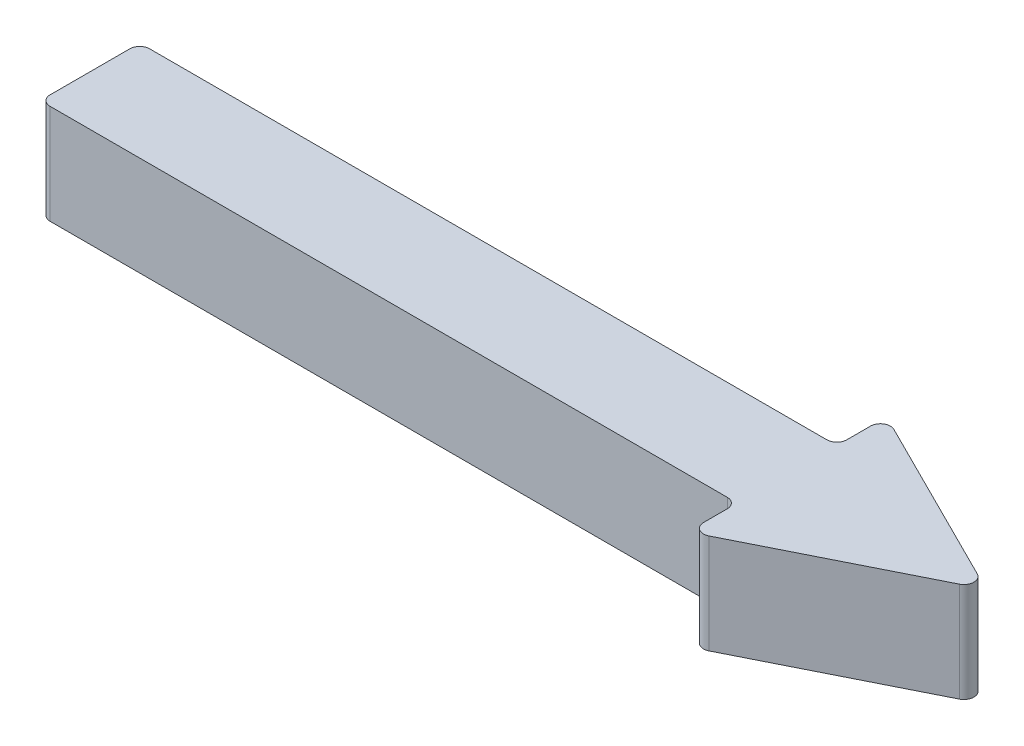
SolidWorks part; units mm, degrees
material "Acrylic (Medium-high impact)"
ref_plane "Front Plane" through (0, 0, 0) normal (0, 0, 1) x (1, 0, 0)
ref_plane "Top Plane" through (0, 0, 0) normal (0, 1, 0) x (1, 0, 0)
ref_plane "Right Plane" through (0, 0, 0) normal (1, 0, 0) x (0, 0, -1)
sketch "Sketch1" plane through (0, 0, 0) normal (0, 1, 0) x (1, 0, 0)
  line L0 (0, 3.175) -> (57.15, 3.175) construction
  line L1 (0, 0) -> (44.45, 0)
  line L2 (0, 0) -> (0, 6.35)
  line L3 (0, 6.35) -> (44.45, 6.35)
  line L4 (44.45, 0) -> (44.45, 6.35)
  line L5 (44.45, -3.175) -> (44.45, 9.525)
  line L6 (44.45, 9.525) -> (57.15, 3.175)
  line L7 (57.15, 3.175) -> (44.45, -3.175)
  point P10 (44.45, 3.175)
  dimension "D1" = 6.35
  dimension "D2" = 44.45
  dimension "D3" = 57.15
  dimension "D4" = 12.7
extrude "Boss-Extrude1" add sketch "Sketch1" along normal blind 6.35 contours L2 L0 L5 L3 | L0 L2 L1 L4 | L5 L0 L6 | L0 L4 L5 L7
sketch "Sketch2" plane through (0, 0, 0) normal (-1, 0, 0) x (0, 0, 1)
  line L0 (-3.175, 0) -> (-3.175, 6.35) construction
  line L1 (0, 6.35) -> (-6.35, 6.35) construction
  line L2 (-6.35, 3.175) -> (0, 3.175) construction
  line L3 (-6.35, 6.35) -> (-6.35, 0) construction
  line L4 (0, 6.35) -> (0, 0) construction
  circle A0 centre (-3.175, 3.175) radius 2.4003
  dimension "D1" = 4.8006
extrude "Cut-Extrude1" cut sketch "Sketch2" against normal blind 8.89
fillet "Fillet1" radius 0.635 7 edges at (44.45, 3.175, -6.35) (44.45, 3.175, 0) (44.45, 3.175, 3.175) (44.45, 3.175, -9.525) (57.15, 3.175, -3.175) (0, 3.175, 0) (0, 3.175, -6.35)
sketch "Sketch4" plane through (0, 0, 0) normal (0, -1, 0) x (1, 0, 0)
  line L0 (0, -3.175) -> (56.3651, -3.175) construction
  line L1 (0, -0.635) -> (0, -5.715) construction
  line L2 (28.1825, -6.35) -> (28.1825, 0)
  line L3 (0.635, 0) -> (43.815, 0) construction
  arc A0 (56.0141, -3.743) -> (56.0141, -2.607) centre (55.7301, -3.175) ccw construction
  circle A1 centre (20.5625, -3.175) radius 0.889
  circle A2 centre (35.8025, -3.175) radius 0.889
  point P12 (28.1825, -3.175)
  dimension "D1" = 1.778
  dimension "D2" = 7.62
extrude "Cut-Extrude2" cut sketch "Sketch4" against normal blind 3.81 contours A2 | A1
